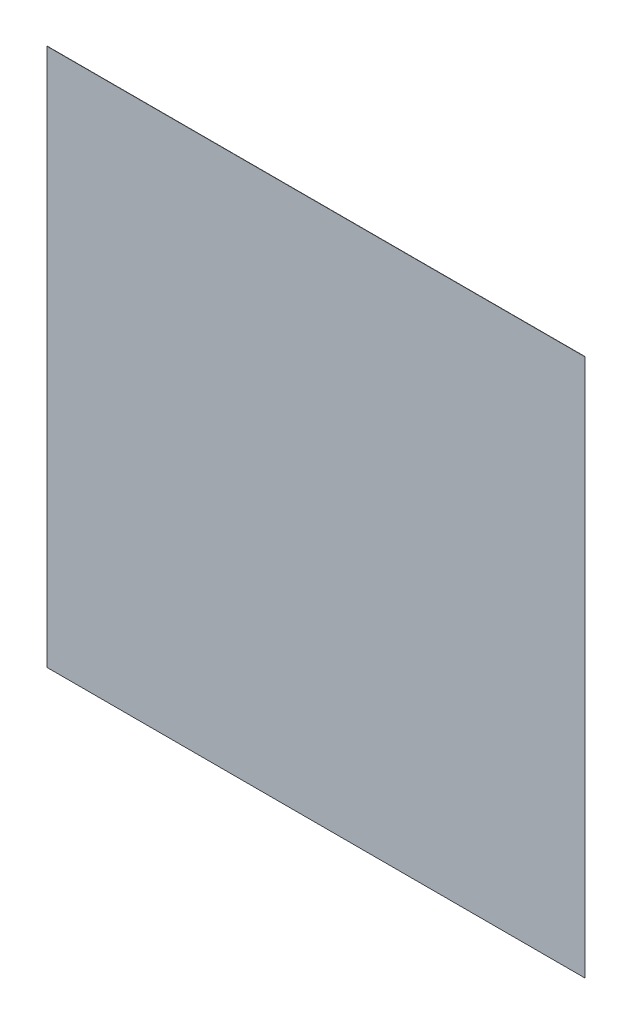
SolidWorks part; units mm, degrees
ref_plane "前视基准面" through (0, 0, 0) normal (0, 0, 1) x (1, 0, 0)
ref_plane "上视基准面" through (0, 0, 0) normal (0, 1, 0) x (1, 0, 0)
ref_plane "右视基准面" through (0, 0, 0) normal (1, 0, 0) x (0, 0, -1)
sketch "草图1" plane through (0, 0, 0) normal (0, 0, 1) x (1, 0, 0)
  line L1 (-110, -110) -> (110, -110)
  line L2 (-110, -110) -> (-110, 110)
  line L3 (-110, 110) -> (110, 110)
  line L4 (110, -110) -> (110, 110)
  line L5 (-110, -110) -> (110, 110) construction
  line L6 (-110, 110) -> (110, -110) construction
  point P0 (0, 0)
  dimension "D1" = 220
extrude "凸台-拉伸1" add sketch "草图1" along normal blind 0.1
